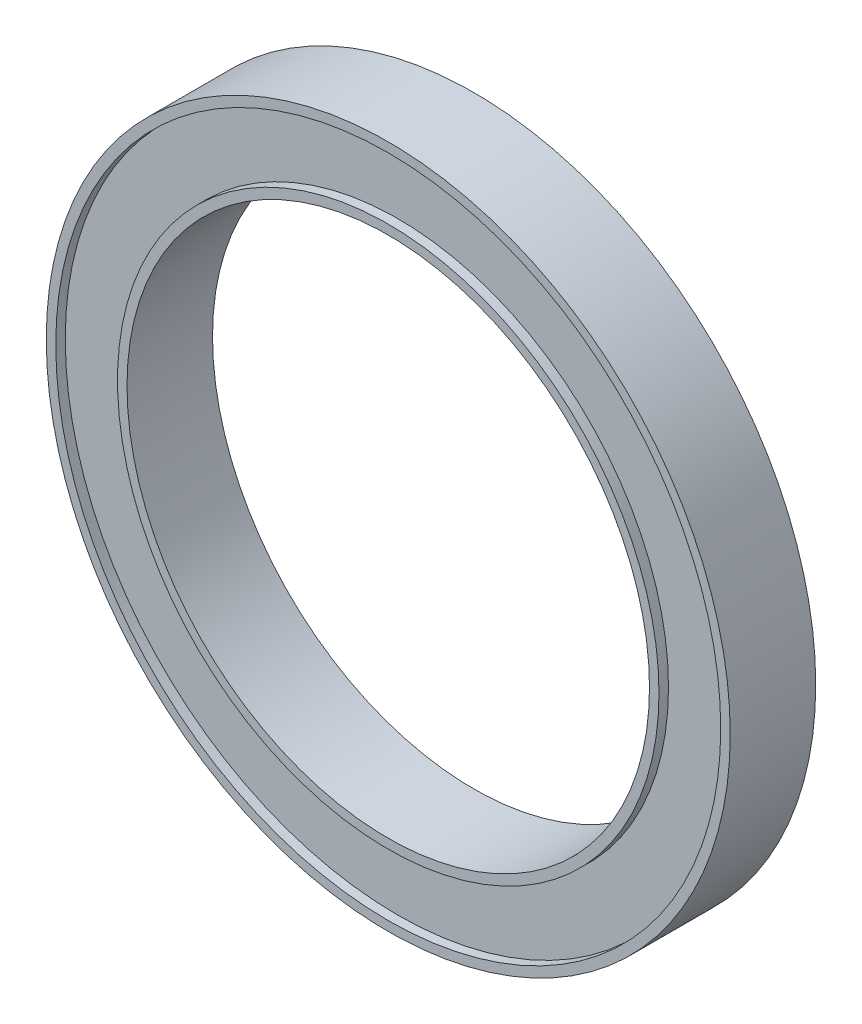
SolidWorks part; units mm, degrees
ref_plane "Front Plane" through (0, 0, 0) normal (0, 0, 1) x (1, 0, 0)
ref_plane "Top Plane" through (0, 0, 0) normal (0, 1, 0) x (1, 0, 0)
ref_plane "Right Plane" through (0, 0, 0) normal (1, 0, 0) x (0, 0, -1)
sketch "Sketch1" plane through (0, 0, 0) normal (0, 0, 1) x (1, 0, 0)
  circle A0 centre (0, 0) radius 36
  circle A1 centre (0, 0) radius 27.5
  dimension "D1" = 72
  dimension "D2" = 55
extrude "Boss-Extrude1" add sketch "Sketch1" along normal mid plane 9
sketch "Sketch3" plane through (0, 0, 4.5) normal (0, 0, 1) x (1, 0, 0)
  circle A0 centre (0, 0) radius 35
  circle A1 centre (0, 0) radius 28.5
  dimension "D1" = 70
  dimension "D2" = 57
extrude "Cut-Extrude1" cut sketch "Sketch3" against normal blind 1
mirror "Mirror1" about plane through (0, 0, 0) normal (0, 0, 1) of "Cut-Extrude1"
